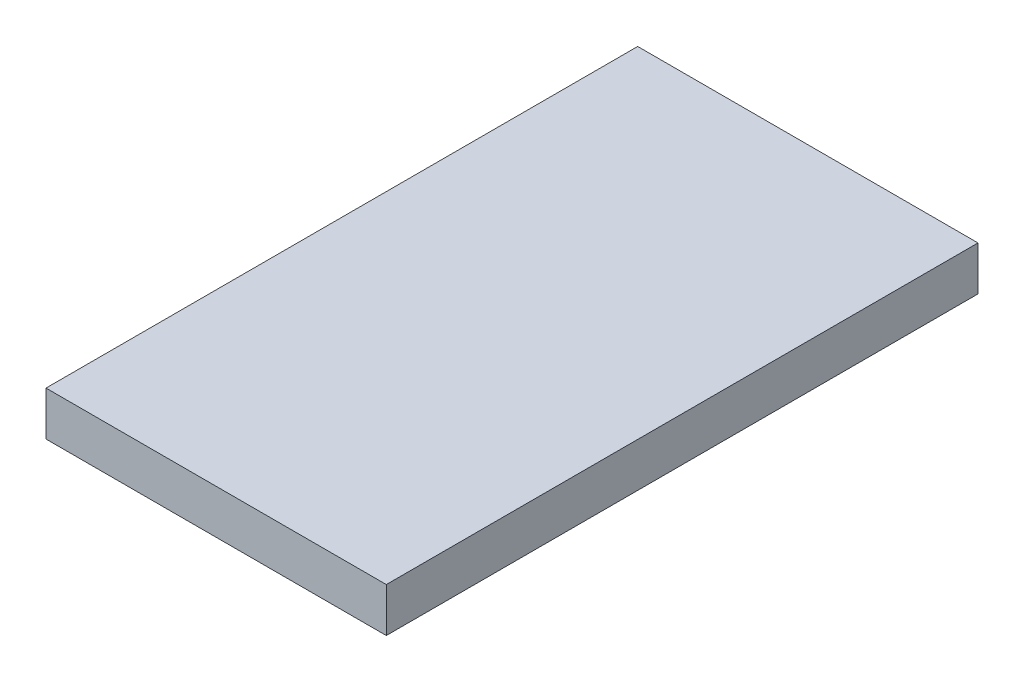
SolidWorks part; units mm, degrees
ref_plane "Front Plane" through (0, 0, 0) normal (0, 0, 1) x (1, 0, 0)
ref_plane "Top Plane" through (0, 0, 0) normal (0, 1, 0) x (1, 0, 0)
ref_plane "Right Plane" through (0, 0, 0) normal (1, 0, 0) x (0, 0, -1)
sketch "Sketch3" plane through (0, 0, 0) normal (0, 0, 1) x (1, 0, 0)
  line L0 (0, 0) -> (58.435, 0)
  line L1 (58.435, 0) -> (58.435, 7.5853)
  line L2 (58.435, 7.5853) -> (0, 7.5853)
  line L3 (0, 7.5853) -> (0, 0)
extrude "Extrude2" add sketch "Sketch3" along normal blind 101.6
